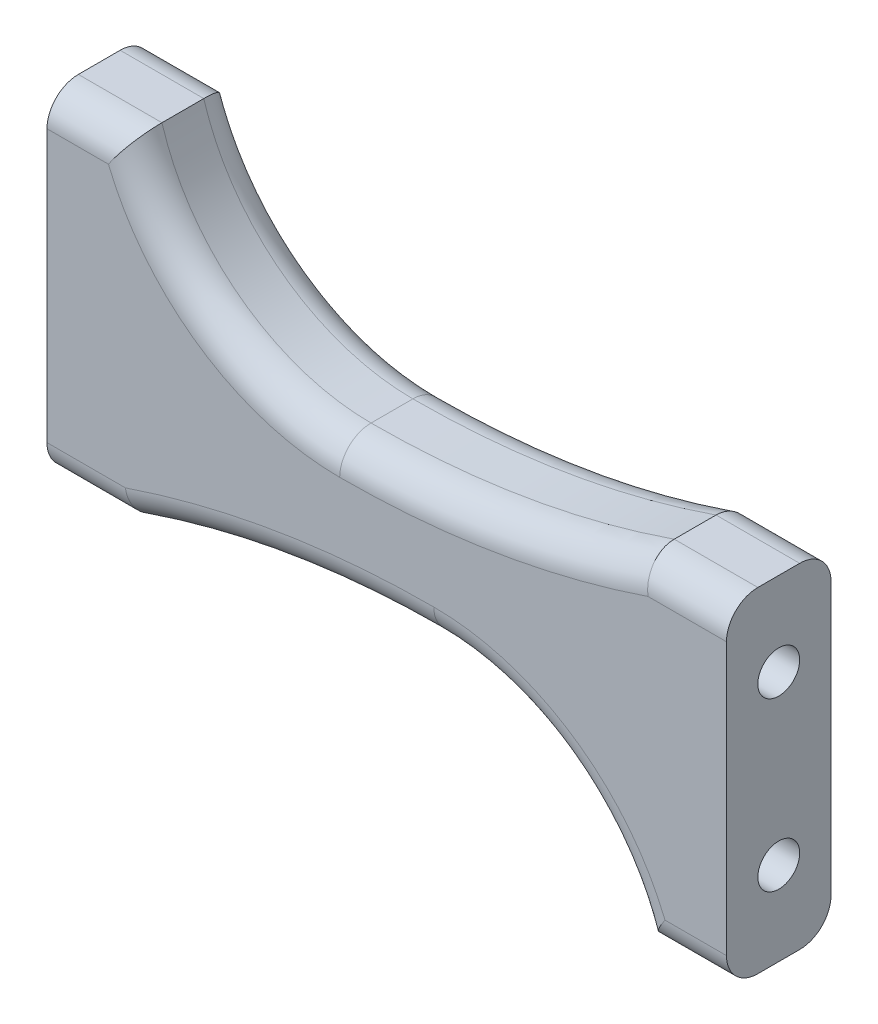
SolidWorks part; units mm, degrees
material "Mahogany"
ref_plane "Front" through (0, 0, 0) normal (0, 0, 1) x (1, 0, 0)
ref_plane "Top" through (0, 0, 0) normal (0, 1, 0) x (1, 0, 0)
ref_plane "Right" through (0, 0, 0) normal (1, 0, 0) x (0, 0, -1)
sketch "Sketch1" plane through (0, 0, 0) normal (0, 0, 1) x (1, 0, 0)
  line L0 (24.4994, -21) -> (32.4994, -21)
  line L1 (-32.5, 21) -> (-24.5, 21)
  line L2 (-32.5, 21) -> (-32.5, -11)
  line L8 (-32.5, -11) -> (-24.5, -11)
  line L9 (32.4994, -21) -> (32.4994, 11)
  line L10 (32.4994, 11) -> (24.4994, 11)
  arc A0 (24.4994, -21) -> (4.5, -6.12) centre (4.5, -27) ccw
  arc A1 (-24.5, 21) -> (-4.5006, 6.12) centre (-4.5006, 27) ccw
  arc A2 (-4.5006, 6.12) -> (24.4994, 11) centre (-4.4993, 94.72) ccw
  arc A3 (4.5, -6.12) -> (-24.5, -11) centre (4.4986, -94.72) ccw
  point P0 (0, 0)
  dimension "D3" = 88.6
  dimension "D5" = 20.88
  dimension "D1" = 21
  dimension "D2" = 21
  dimension "D4" = 32
  dimension "D6" = 37
  dimension "D7" = 32
  dimension "D8" = 37
  dimension "D9" = 8
  dimension "D10" = 16
  dimension "D11" = 32.5
extrude "Boss-Extrude1" add sketch "Sketch1" along normal mid plane 10
fillet "Fillet1" radius 3 16 edges at (-10.2039, -7.3484, 5) (-10.2039, -7.3484, -5) (-16.9645, 10.2481, -5) (-16.9645, 10.2481, 5) (-28.5, -11, -5) (-28.5, -11, 5) (16.9638, -10.2481, 5) (28.4994, -21, 5) (28.4994, -21, -5) (16.9638, -10.2481, -5) (-28.5, 21, -5) (28.4994, 11, -5) (10.2032, 7.3484, -5) (28.4994, 11, 5) (-28.5, 21, 5) (10.2032, 7.3484, 5)
sketch "Sketch2" plane through (32.4994, 0, 0) normal (1, 0, 0) x (0, 0, -1)
  line L0 (-2, -21) -> (2, -21) construction
  circle A0 centre (0, -13) radius 2
  circle A1 centre (0, 3) radius 2
  dimension "D1" = 4
  dimension "D2" = 8
  dimension "D3" = 24
extrude "Cut-Extrude1" cut sketch "Sketch2" against normal blind 7
sketch "Sketch3" plane through (-32.5, 0, 0) normal (-1, 0, 0) x (0, 0, 1)
  line L0 (2, 21) -> (-2, 21) construction
  circle A0 centre (0, 13) radius 2
  circle A1 centre (0, -3) radius 2
  dimension "D1" = 4
  dimension "D2" = 8
  dimension "D3" = 24
extrude "Cut-Extrude2" cut sketch "Sketch3" against normal blind 7
